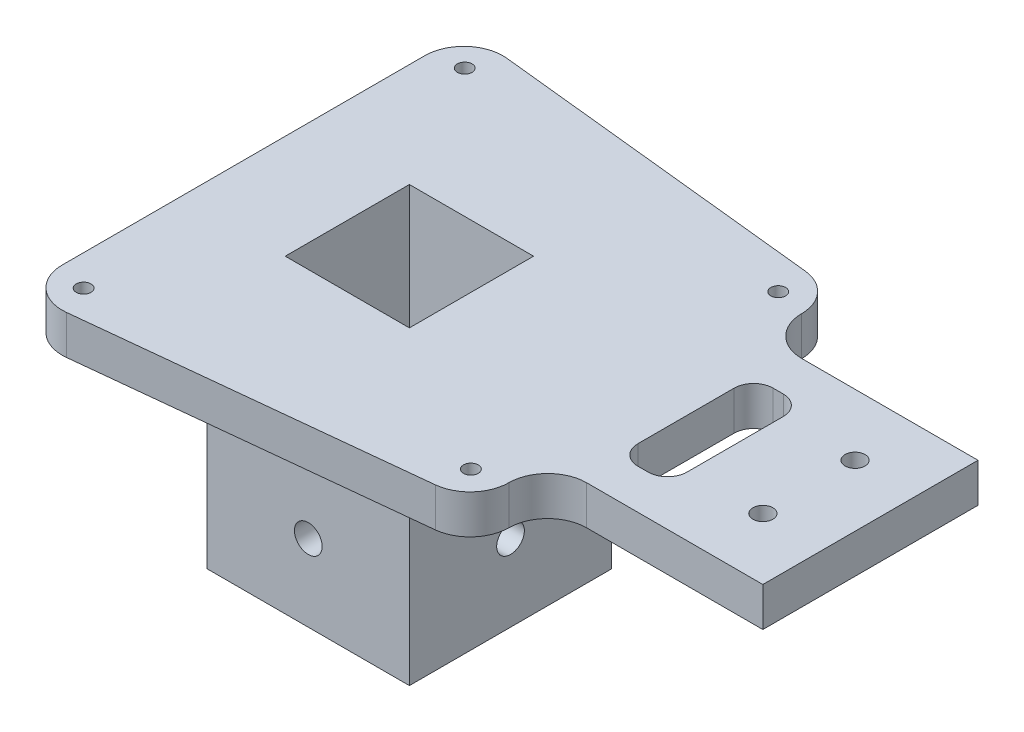
SolidWorks part; units mm, degrees
ref_plane "Front Plane" through (0, 0, 0) normal (0, 0, 1) x (1, 0, 0)
ref_plane "Top Plane" through (0, 0, 0) normal (0, 1, 0) x (1, 0, 0)
ref_plane "Right Plane" through (0, 0, 0) normal (1, 0, 0) x (0, 0, -1)
sketch "Sketch1" plane through (0, 0, 0) normal (0, 1, 0) x (1, 0, 0)
  line L0 (-16.45, -16.45) -> (-16.45, 16.45)
  line L1 (-10.1, -10.1) -> (10.1, -10.1)
  line L2 (-10.1, -10.1) -> (-10.1, 10.1)
  line L3 (-10.1, 10.1) -> (10.1, 10.1)
  line L4 (10.1, -10.1) -> (10.1, 10.1)
  line L5 (-10.1, -10.1) -> (10.1, 10.1) construction
  line L6 (-10.1, 10.1) -> (10.1, -10.1) construction
  line L7 (-16.45, 16.45) -> (16.45, 16.45)
  line L8 (16.45, -16.45) -> (16.45, 16.45)
  line L9 (-16.45, -16.45) -> (16.45, -16.45)
  point P0 (0, 0)
  dimension "D1" = 20.2
  dimension "D2" = 20.2
  dimension "D3" = 6.35
extrude "Boss-Extrude1" add sketch "Sketch1" along normal blind 25
sketch "Sketch2" plane through (0, 0, 16.45) normal (0, 0, 1) x (1, 0, 0)
  line L0 (-16.45, 25) -> (16.45, 0)
  point P4 (0, 12.5)
hole_wizard "M4 Clearance Hole1" positions "Sketch3" profile "Sketch4" hole size "M4" standard "ANSI Metric" end condition through all
sketch "Sketch3" plane through (0, 0, 16.45) normal (0, 0, 1) x (1, 0, 0)
  point P0 (0, 12.5)
sketch "Sketch4" plane through (0, 12.5, 16.45) normal (1, 0, 0) x (0, -1, 0)
  line L0 (0, 0) -> (0, 32.9)
  line L1 (0, 32.9) -> (2.25, 32.9)
  line L2 (2.25, 32.9) -> (2.25, 0)
  line L5 (2.25, 0) -> (0, 0)
  line L11 (0, -6.35) -> (0, 107.95) construction
  dimension "Thru Hole Dia." = 4.5
  dimension "Thru Hole Depth" = 32.9
sketch "Sketch5" plane through (16.45, 0, 0) normal (1, 0, 0) x (0, 0, -1)
  line L0 (-16.45, 0) -> (16.45, 25)
  point P4 (0, 12.5)
hole_wizard "M4 Clearance Hole2" positions "Sketch6" profile "Sketch7" hole size "M4" standard "ANSI Metric" end condition through all
sketch "Sketch6" plane through (16.45, 0, 0) normal (1, 0, 0) x (0, 0, -1)
  point P0 (0, 12.5)
sketch "Sketch7" plane through (16.45, 12.5, 0) normal (0, 1, 0) x (0, 0, -1)
  line L0 (0, 0) -> (0, 32.9)
  line L1 (0, 32.9) -> (2.25, 32.9)
  line L2 (2.25, 32.9) -> (2.25, 0)
  line L5 (2.25, 0) -> (0, 0)
  line L11 (0, -6.35) -> (0, 107.95) construction
  dimension "Thru Hole Dia." = 4.5
  dimension "Thru Hole Depth" = 32.9
sketch "Sketch8" plane through (0, 25, 0) normal (0, 1, 0) x (1, 0, 0)
  line L1 (16.45, 16.45) -> (-16.45, 16.45)
  line L2 (16.45, 16.45) -> (16.45, -16.45)
  line L3 (16.45, -16.45) -> (-16.45, -16.45)
  line L4 (-16.45, 16.45) -> (-16.45, -16.45)
  line L5 (16.45, 16.45) -> (-16.45, -16.45) construction
  line L6 (16.45, -16.45) -> (-16.45, 16.45) construction
  line L7 (10.1, 10.1) -> (-10.1, 10.1)
  line L8 (10.1, 10.1) -> (10.1, -10.1)
  line L9 (10.1, -10.1) -> (-10.1, -10.1)
  line L10 (-10.1, 10.1) -> (-10.1, -10.1)
  line L11 (10.1, 10.1) -> (-10.1, -10.1) construction
  line L12 (10.1, -10.1) -> (-10.1, 10.1) construction
  point P0 (0, 0)
  point P7 (0, 0)
extrude "Boss-Extrude2" add sketch "Sketch8" along normal blind 12.7
sketch "Sketch9" plane through (0, 37.7, 0) normal (0, 1, 0) x (1, 0, 0)
  line L0 (43.7, -41.2) -> (-43.7, -41.2)
  line L1 (31, 28.5) -> (-31, 28.5)
  line L3 (31, -28.5) -> (-31, -28.5)
  line L4 (-31, 28.5) -> (-31, -28.5)
  line L5 (31, 28.5) -> (-31, -28.5) construction
  line L6 (31, -28.5) -> (-31, 28.5) construction
  line L7 (-43.7, 41.2) -> (-43.7, -41.2)
  line L8 (43.7, 41.2) -> (-43.7, 41.2)
  line L9 (43.7, 41.2) -> (43.7, -41.2)
  line L10 (31, 28.5) -> (31, -28.5) construction
  point P0 (0, 0)
  point P11 (-31, -28.5)
  point P12 (31, -28.5)
  point P13 (-31, 28.5)
  point P14 (31, 28.5)
  dimension "D1" = 62
  dimension "D2" = 57
  dimension "D3" = 12.7
extrude "Boss-Extrude3" add sketch "Sketch9" along normal blind 6.35
sketch "Sketch10" plane through (0, 44.05, 0) normal (0, 1, 0) x (1, 0, 0)
  line L1 (0, 0) -> (35, 0)
  line L2 (0, 0) -> (0, -25)
  line L3 (0, -25) -> (35, -25)
  line L4 (35, 0) -> (35, -25)
  line L5 (0, 0) -> (-22, 0)
  line L6 (0, 0) -> (0, -31)
  line L7 (0, -31) -> (-22, -31)
  line L8 (-22, 0) -> (-22, -31)
  line L9 (0, 0) -> (35, 0)
  line L10 (0, 0) -> (0, 25)
  line L11 (0, 25) -> (35, 25)
  line L12 (35, 0) -> (35, 25)
  line L13 (0, 0) -> (-22, 0)
  line L14 (0, 0) -> (0, 31)
  line L15 (0, 31) -> (-22, 31)
  line L16 (-22, 0) -> (-22, 31)
  point P13 (35, -25)
  point P14 (35, 25)
  point P15 (-22, 31)
  point P16 (-22, -31)
  dimension "D1" = 35
  dimension "D2" = 25
  dimension "D3" = 22
  dimension "D4" = 31
  dimension "D5" = 25
  dimension "D6" = 31
hole_wizard "M2 Clearance Hole1" positions "Sketch11" profile "Sketch12" hole size "M2" standard "ANSI Metric" end condition through all
sketch "Sketch11" plane through (0, 44.05, 0) normal (0, 1, 0) x (1, 0, 0)
  point P0 (35, -25)
  point P3 (-22, -31)
  point P6 (-22, 31)
  point P9 (35, 25)
sketch "Sketch12" plane through (35, 44.05, 25) normal (1, 0, 0) x (0, 0, 1)
  line L0 (0, 0) -> (0, 44.05)
  line L1 (0, 44.05) -> (1.2, 44.05)
  line L2 (1.2, 44.05) -> (1.2, 0)
  line L5 (1.2, 0) -> (0, 0)
  line L11 (0, -6.35) -> (0, 107.95) construction
  dimension "Thru Hole Dia." = 2.4
  dimension "Thru Hole Depth" = 44.05
sketch "Sketch13" plane through (0, 37.7, 0) normal (0, -1, 0) x (1, 0, 0)
  line L1 (-10.1, -10.1) -> (10.1, -10.1)
  line L2 (-10.1, -10.1) -> (-10.1, 10.1)
  line L3 (-10.1, 10.1) -> (10.1, 10.1)
  line L4 (10.1, -10.1) -> (10.1, 10.1)
extrude "Cut-Extrude1" cut sketch "Sketch13" against normal through all
sketch "Sketch14" plane through (0, 44.05, 0) normal (0, 1, 0) x (1, 0, 0)
  line L0 (35, -25) -> (-22, -31) construction
  line L1 (-22, -31) -> (-22, 31) construction
  line L2 (-22, 31) -> (35, 25) construction
  line L3 (35, 25) -> (35, -25) construction
  line L4 (40, 23.7846) -> (40, -23.7846)
  line L5 (34.3147, -30.0998) -> (-19.9853, -35.8155)
  line L6 (-27, -29.5004) -> (-27, 29.5004)
  line L7 (-19.9853, 35.8155) -> (34.3147, 30.0998)
  line L8 (-43.7, 41.2) -> (-43.7, -41.2) construction
  line L9 (-43.7, 41.2) -> (-43.7, -41.2)
  line L10 (43.7, 41.2) -> (-43.7, 41.2) construction
  line L11 (43.7, 41.2) -> (-43.7, 41.2)
  line L12 (43.7, 41.2) -> (43.7, -41.2) construction
  line L13 (43.7, 41.2) -> (43.7, -41.2)
  line L14 (40, 29.5013) -> (40, -29.5013) construction
  line L15 (-27, 36.5539) -> (40, 29.5013) construction
  line L16 (-27, -36.5539) -> (-27, 36.5539) construction
  line L17 (40, -29.5013) -> (-27, -36.5539) construction
  arc A0 (40, 23.7846) -> (34.3147, 30.0998) centre (33.65, 23.7846) ccw
  arc A1 (-27, 29.5004) -> (-19.9853, 35.8155) centre (-20.65, 29.5004) cw
  arc A2 (-19.9853, -35.8155) -> (-27, -29.5004) centre (-20.65, -29.5004) cw
  arc A3 (40, -23.7846) -> (34.3147, -30.0998) centre (33.65, -23.7846) cw
  line M17 (43.7, -41.2) -> (43.7, 41.2)
  line M18 (43.7, 41.2) -> (-43.7, 41.2)
  line M19 (-43.7, 41.2) -> (-43.7, -41.2)
  line M20 (-43.7, -41.2) -> (43.7, -41.2)
  dimension "D2" = 6.35
  dimension "D1" = 5
extrude "Cut-Extrude2" cut sketch "Sketch14" against normal through all contours L4 A3 L5 A2 L6 A1 L7 A0 M20 M17 M18 M19
sketch "Sketch15" plane through (0, 44.05, 0) normal (0, 1, 0) x (1, 0, 0)
  line L0 (40, 0) -> (75, 0) construction
  line L1 (40, 23.7846) -> (40, -23.7846) construction
  line L2 (65, -7.5) -> (65, 7.5) construction
  line L3 (75, -17.5) -> (40, -17.5)
  line L4 (75, -17.5) -> (75, 17.5)
  line L5 (75, 17.5) -> (40, 17.5)
  line L6 (40, -17.5) -> (40, 17.5)
  line L7 (75, -17.5) -> (40, 17.5) construction
  line L8 (75, 17.5) -> (40, -17.5) construction
  circle A0 centre (65, 7.5) radius 1.625
  circle A1 centre (65, -7.5) radius 1.625
  point P5 (57.5, 0)
  point P13 (65, 0)
  dimension "D3" = 3.25
  dimension "D1" = 35
  dimension "D2" = 35
  dimension "D4" = 15
  dimension "D5" = 10
extrude "Boss-Extrude4" add sketch "Sketch15" against normal up to surface (6.35 mm away) up to face at (0, 37.7, 0)
fillet "Fillet1" radius 6.35 2 edges at (40, 40.875, 17.5) (40, 40.875, -17.5)
sketch "Sketch16" plane through (0, 44.05, 0) normal (0, 1, 0) x (1, 0, 0)
  line L0 (80, 0) -> (-49920, 0) construction
  line L1 (75, -17.5) -> (75, 17.5) construction
  line L3 (53, 11) -> (45, 11)
  line L4 (53, 11) -> (53, -11)
  line L5 (53, -11) -> (45, -11)
  line L6 (45, 11) -> (45, -11)
  line L7 (53, 11) -> (45, -11) construction
  line L8 (53, -11) -> (45, 11) construction
  circle A0 centre (65, 7.5) radius 1.625 construction
  point P4 (75, 0)
  point P5 (49, 0)
  dimension "D1" = 22
  dimension "D2" = 8
  dimension "D3" = 12
extrude "Cut-Extrude3" cut sketch "Sketch16" against normal through all
fillet "Fillet2" radius 3.175 4 edges at (45, 40.875, -11) (53, 40.875, -11) (53, 40.875, 11) (45, 40.875, 11)
